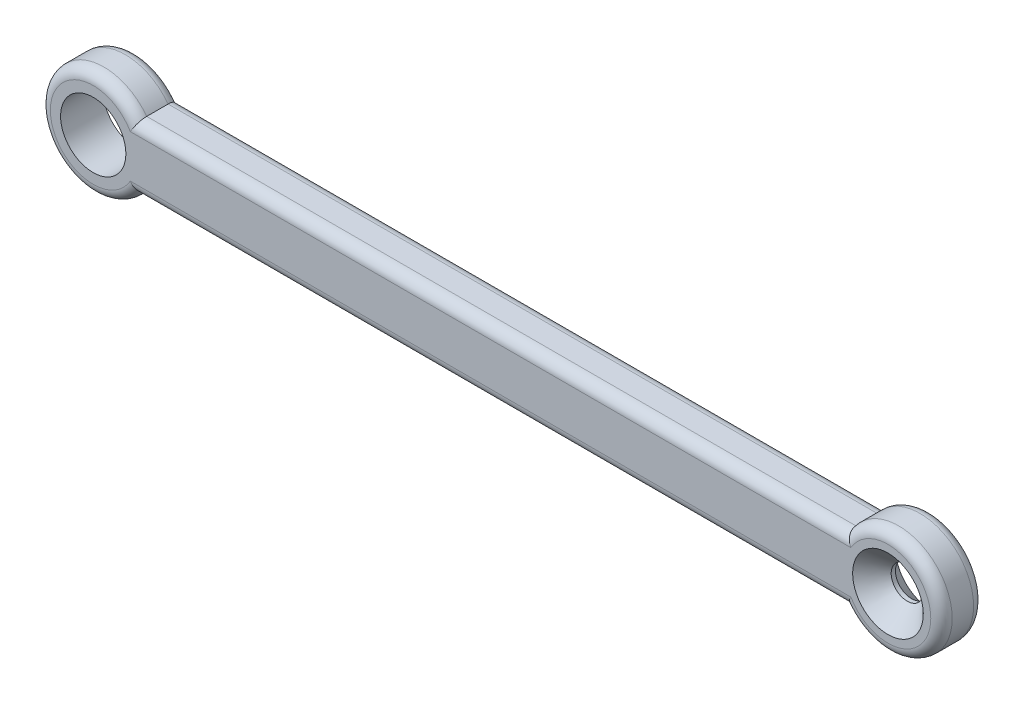
SolidWorks part; units mm, degrees
ref_plane "Plan de face" through (0, 0, 0) normal (0, 0, 1) x (1, 0, 0)
ref_plane "Plan de dessus" through (0, 0, 0) normal (0, 1, 0) x (1, 0, 0)
ref_plane "Plan de droite" through (0, 0, 0) normal (1, 0, 0) x (0, 0, -1)
ref_plane "Plan1" through (0, 2, 0) normal (0, 1, 0) x (1, 0, 0)
sketch "Esquisse1" plane through (0, 2, 0) normal (0, 0, -1) x (1, 0, 0)
  line L0 (47.7089, 2) -> (0, 2) construction
  line L1 (-47.7089, 5) -> (0, 5) construction
  line L2 (0, 9.7076) -> (0, -6.7613) construction
  line L3 (-47.7089, 2) -> (0, 2) construction
  line L4 (-33.125, -1) -> (33.125, -1)
  line L5 (-33.125, 5) -> (33.125, 5)
  line L6 (-47.7089, -1) -> (0, -1) construction
  arc A0 (33.125, 5) -> (33.125, -1) centre (37.125, 2) cw
  arc A1 (-33.125, 5) -> (-33.125, -1) centre (-37.125, 2) ccw
  dimension "D1" = 74.25
  dimension "D2" = 5
  dimension "D3" = 3
  dimension "D4" = 3
extrude "Boss.-Extru.1" add sketch "Esquisse1" against normal blind 4
hole_wizard "Diamètre du perçage Ø6.1 (6.1)1" positions "Esquisse3" profile "Esquisse2" hole size "Ø6.1" standard "Ansi Metric" end condition through all
sketch "Esquisse3" plane through (0, 0, 4) normal (0, 0, 1) x (-1, 0, 0)
  point P0 (37.125, 0)
sketch "Esquisse2" plane through (-37.125, 0, 4) normal (1, 0, 0) x (0, -1, 0)
  line L0 (0, 0) -> (0, 4)
  line L1 (0, 4) -> (3.05, 4)
  line L2 (3.05, 4) -> (3.05, 0)
  line L5 (3.05, 0) -> (0, 0)
  line L11 (0, -6.35) -> (0, 107.95) construction
  dimension "Diamètre du perçage jusqu'au prochain" = 6.1
  dimension "Profondeur du perçage jusqu'au prochain" = 4
hole_wizard "Fraisage pour vis à tête fraisée M2.51" positions "Esquisse5" profile "Esquisse4" countersink size "M2.5" standard "Ansi Metric" end condition through all
sketch "Esquisse5" plane through (0, 0, 4) normal (0, 0, 1) x (-1, 0, 0)
  point P0 (-37.125, 0)
sketch "Esquisse4" plane through (37.125, 0, 4) normal (1, 0, 0) x (0, -1, 0)
  line L0 (0, 0) -> (0, 4)
  line L1 (0, 4) -> (3.3, 4)
  line L2 (1.5, 2.2) -> (1.5, 1.8)
  line L3 (1.5, 1.8) -> (3.3, 0)
  line L5 (3.3, 0) -> (0, 0)
  line L6 (-1.5, 1.8) -> (-3.3, 0) construction
  line L7 (3.3, 4) -> (1.5, 2.2)
  line L8 (-3.3, 4) -> (-1.5, 2.2) construction
  line L11 (0, -6.35) -> (0, 107.95) construction
  dimension "Diamètre du perçage jusqu'au prochain" = 3
  dimension "Profondeur du perçage jusqu'au prochain" = 4
  dimension "Diamètre du fraisage entrant" = 6.6
  dimension "Angle du fraisage entrant" = 90
  dimension "Diamètre du fraisage débouchant" = 6.6
  dimension "Angle du fraisage débouchant" = 90
fillet "Congé1" radius 1 8 edges at (-42.125, 0, 4) (-42.125, 0, 0) (0, 3, 4) (0, -3, 4) (42.125, 0, 4) (42.125, 0, 0) (0, 3, 0) (0, -3, 0)
